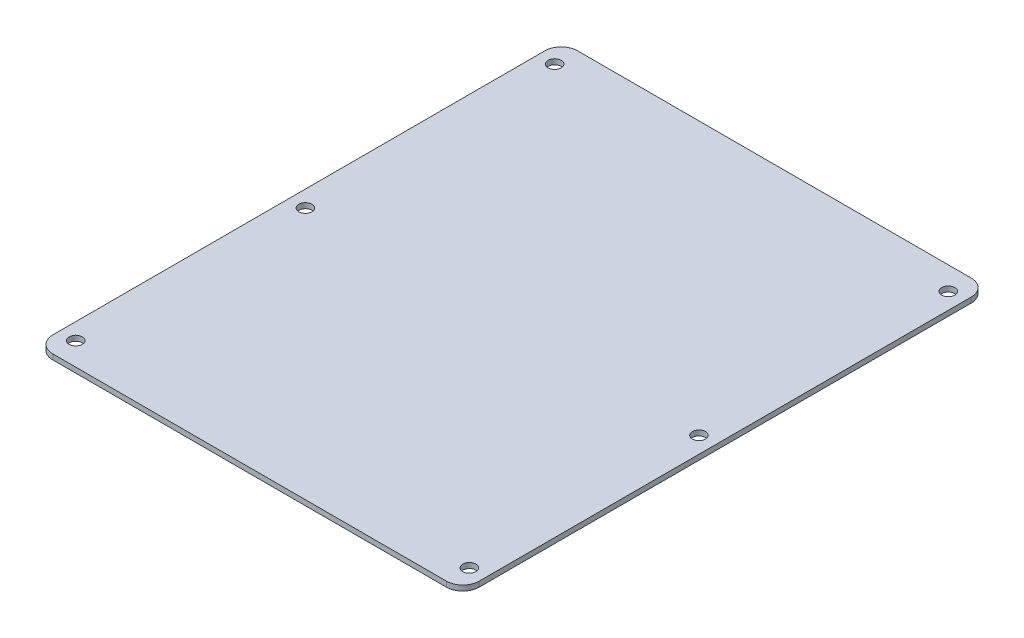
SolidWorks part; units mm, degrees
material "3003-H16"
ref_plane "Plan de face" through (0, 0, 0) normal (0, 0, 1) x (1, 0, 0)
ref_plane "Plan de dessus" through (0, 0, 0) normal (0, 1, 0) x (1, 0, 0)
ref_plane "Plan de droite" through (0, 0, 0) normal (1, 0, 0) x (0, 0, -1)
sketch "Esquisse1" plane through (0, 0, 0) normal (0, 1, 0) x (1, 0, 0)
  line L1 (-65, 80) -> (65, 80)
  line L2 (-65, 80) -> (-65, -80)
  line L3 (-65, -80) -> (65, -80)
  line L4 (65, 80) -> (65, -80)
  line L5 (-65, 80) -> (65, -80) construction
  line L6 (-65, -80) -> (65, 80) construction
  point P0 (0, 0)
  dimension "D1" = 160
  dimension "D2" = 130
extrude "Boss.-Extru.1" add sketch "Esquisse1" along normal blind 1.6
sketch "Esquisse2" plane through (0, 1.6, 0) normal (0, 1, 0) x (1, 0, 0)
  line L0 (-60, 80) -> (-60, 73) construction
  line L1 (65, 80) -> (-65, 80) construction
  line L2 (-65, 73) -> (-60, 73) construction
  line L3 (-65, 80) -> (-65, -80) construction
  line L4 (-60, 73) -> (-60, -3) construction
  line L5 (-60, -80) -> (-60, -73) construction
  line L6 (-65, -80) -> (65, -80) construction
  line L7 (0, 0) -> (0, 80) construction
  circle A0 centre (-60, 73) radius 2
  circle A1 centre (-60, -3) radius 2
  circle A2 centre (-60, -73) radius 2
  circle A3 centre (60, -73) radius 2
  circle A4 centre (60, -3) radius 2
  circle A5 centre (60, 73) radius 2
  dimension "D3" = 4
  dimension "D5" = 4
  dimension "D7" = 4
  dimension "D1" = 7
  dimension "D2" = 5
  dimension "D4" = 76
  dimension "D6" = 7
extrude "Enlèv. mat.-Extru.1" cut sketch "Esquisse2" against normal through all
fillet "Congé1" radius 5 4 edges at (65, 0.8, -80) (-65, 0.8, -80) (-65, 0.8, 80) (65, 0.8, 80)
